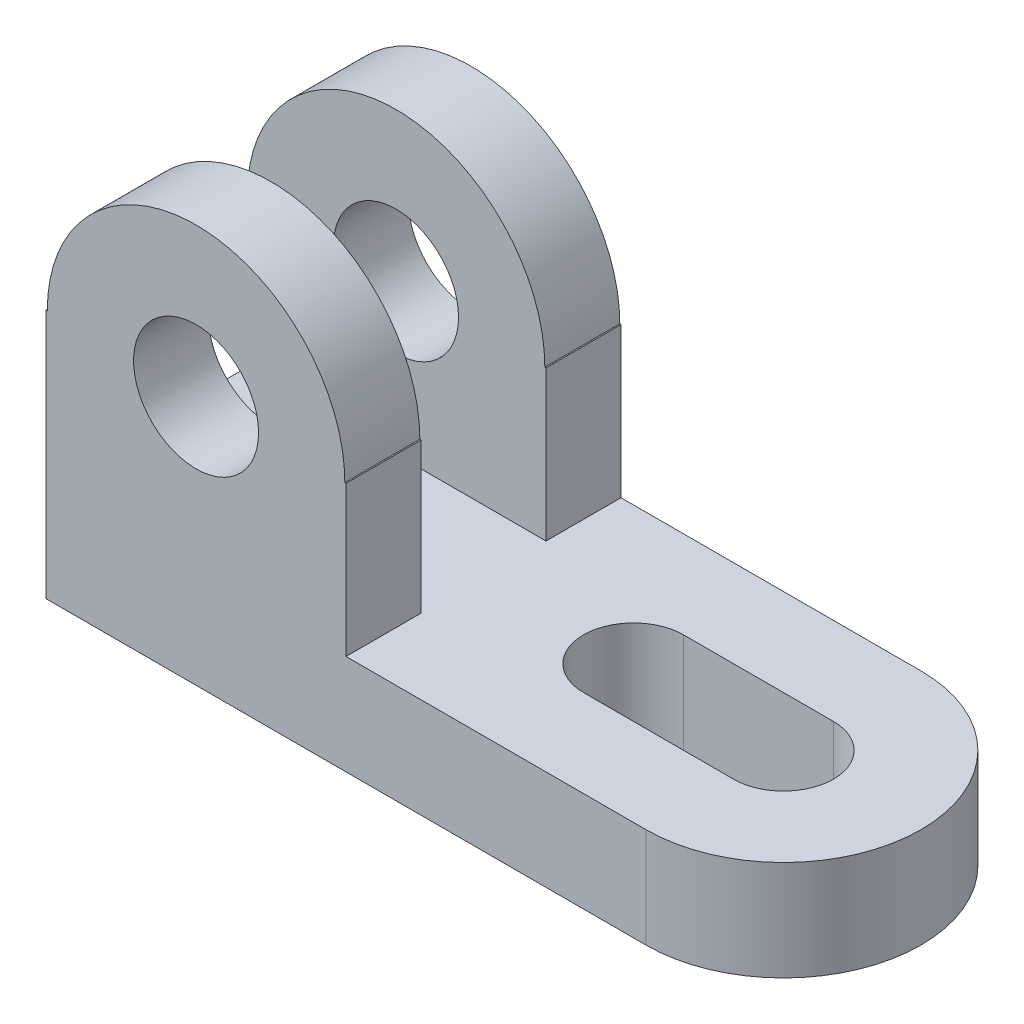
SolidWorks part; units mm, degrees
ref_plane "Front Plane" through (0, 0, 0) normal (0, 0, 1) x (1, 0, 0)
ref_plane "Top Plane" through (0, 0, 0) normal (0, 1, 0) x (1, 0, 0)
ref_plane "Right Plane" through (0, 0, 0) normal (1, 0, 0) x (0, 0, -1)
sketch "Sketch1" plane through (0, 0, 0) normal (0, 1, 0) x (1, 0, 0)
  line L1 (-59, 22) -> (59, 22)
  line L2 (-59, 22) -> (-59, -22)
  line L3 (-59, -22) -> (59, -22)
  line L4 (59, 22) -> (59, -22)
  line L5 (-59, 22) -> (59, -22) construction
  line L6 (-59, -22) -> (59, 22) construction
  circle A0 centre (37, 0) radius 22
  point P0 (0, 0)
  dimension "D1" = 118
  dimension "D2" = 44
extrude "Boss-Extrude1" add sketch "Sketch1" along normal blind 16 contours A0 L1 L2 L3 | A0
sketch "Sketch2" plane through (0, 16, 0) normal (0, 1, 0) x (1, 0, 0)
  line L0 (37, 0) -> (13, 0) construction
  line L1 (37, -8) -> (13, -8)
  line L2 (37, 8) -> (13, 8)
  arc A0 (37, -8) -> (37, 8) centre (37, 0) ccw
  arc A1 (13, 8) -> (13, -8) centre (13, 0) ccw
  point P4 (25, 0)
  dimension "D1" = 24
  dimension "D2" = 16
extrude "Cut-Extrude1" cut sketch "Sketch2" against normal blind 16
sketch "Sketch3" plane through (0, 0, 22) normal (0, 0, 1) x (1, 0, 0)
  line L0 (-59, 0) -> (37, 0) construction
  line L1 (-59, 16) -> (-11, 16)
  line L2 (-59, 16) -> (-59, 40)
  line L3 (-59, 40) -> (-11, 40)
  line L4 (-11, 16) -> (-11, 40)
  circle A0 centre (-35, 40) radius 23.8079
  circle A1 centre (-35, 40) radius 10
  line M6 (37, 16) -> (-59, 16)
  dimension "D3" = 20
  dimension "D1" = 40
  dimension "D2" = 48
extrude "Boss-Extrude2" add sketch "Sketch3" against normal blind 12 contours A1 L3 A0 | A1 L3 A0 | A0 L3 L2 L4 M6
mirror "Mirror1" about plane through (0, 0, 0) normal (0, 0, 1) of "Boss-Extrude2"
